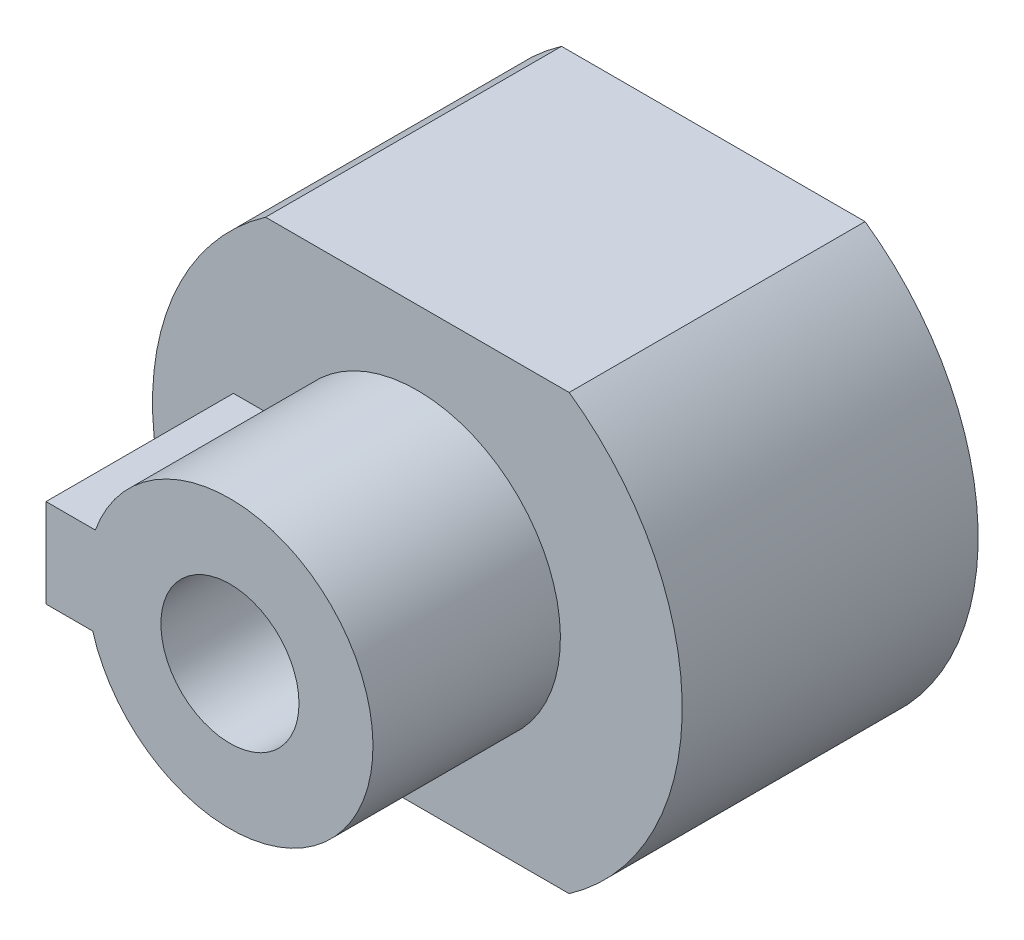
SolidWorks part; units mm, degrees
ref_plane "Front Plane" through (0, 0, 0) normal (1, 0, 0) x (0, 1, 0)
ref_plane "Top Plane" through (0, 0, 0) normal (0, 0, 1) x (0, 1, 0)
ref_plane "Right Plane" through (0, 0, 0) normal (0, 1, 0) x (-1, 0, 0)
sketch "Sketch1" plane through (0, 0, 0) normal (0, 0, 1) x (0, 1, 0)
  line L0 (-4.4, -3.0771) -> (-4.4, 3.0771)
  line L2 (-1.9, -2.15) -> (-1.9, 2.15)
  line L4 (1.9, -2.15) -> (1.9, 2.15)
  line L5 (4.4, -3.0771) -> (4.4, 3.0771)
  arc A0 (-1.9, 2.15) -> (1.9, 2.15) centre (0, 0) cw
  arc A1 (-1.9, -2.15) -> (1.9, -2.15) centre (0, 0) ccw
  arc A2 (-4.4, 3.0771) -> (4.4, 3.0771) centre (0, 0) cw
  arc A3 (-4.4, -3.0771) -> (4.4, -3.0771) centre (0, 0) ccw
  point P0 (0, 0)
  dimension "D3" = 0
  dimension "D4" = 0
  dimension "D1" = 4.3
  dimension "D2" = 3.8
  dimension "D5" = 3.8
  dimension "D6" = 2.5
extrude "Boss-Extrude1" add sketch "Sketch1" along normal blind 6 contours L0 A3 L5 A2 A1 L2 A0 L4
sketch "Sketch2" plane through (0, 0, 6) normal (0, 0, 1) x (1, 0, 0)
  line L0 (-3.7289, -0.8185) -> (-3.7289, 0.9815)
  line L1 (-3.7289, -0.8185) -> (-2.7821, -0.8185)
  line L2 (-3.7289, 0.9815) -> (-2.7289, 0.9815)
  arc A0 (-2.7821, -0.8185) -> (-2.7289, 0.9815) centre (0, 0) ccw
  dimension "D3" = 2.9
  dimension "D1" = 1.8
  dimension "D2" = 1
extrude "Boss-Extrude2" add sketch "Sketch2" along normal blind 3.8
sketch "Sketch3" plane through (0, 0, 9.8) normal (0, 0, 1) x (1, 0, 0)
  circle A0 centre (0, 0) radius 1.4
  arc A1 (-2.7821, -0.8185) -> (-2.7289, 0.9815) centre (0, 0) ccw construction
  dimension "D1" = 1.5
extrude "Cut-Extrude1" cut sketch "Sketch3" against normal through all contours A0
